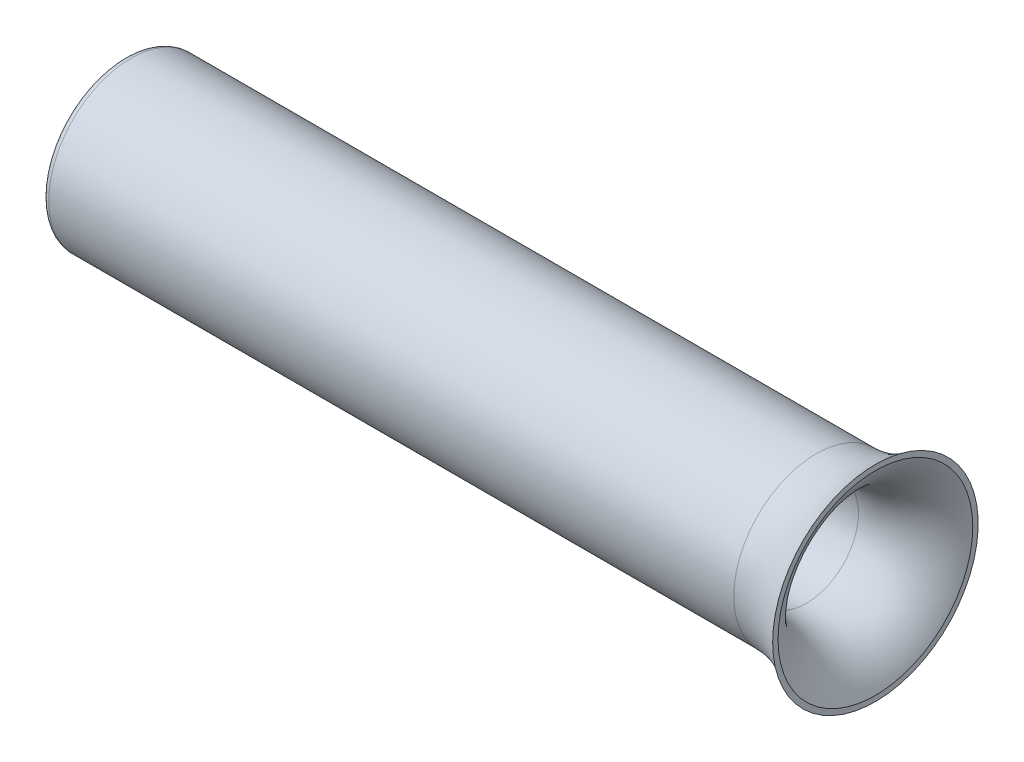
SolidWorks part; units mm, degrees
ref_plane "Front Plane" through (0, 0, 0) normal (0, 0, 1) x (1, 0, 0)
ref_plane "Top Plane" through (0, 0, 0) normal (0, 1, 0) x (1, 0, 0)
ref_plane "Right Plane" through (0, 0, 0) normal (1, 0, 0) x (0, 0, -1)
sketch "Sketch1" plane through (0, 0, 0) normal (0, 0, 1) x (1, 0, 0)
  line L0 (0, 3.95) -> (57, 3.95)
  line L1 (57, 3.95) -> (57, 7.8)
  line L2 (0, 3.95) -> (0, 6.25)
  line L3 (0, 6.25) -> (52.5, 6.25)
  line L6 (0, 0) -> (20.2034, 0) construction
  arc A0 (57, 7.8) -> (52.5, 6.25) centre (52.5, 13.5573) cw
  arc A1 (57, 7.3916) -> (51.7648, 3.95) centre (51.7648, 9.6526) cw
  dimension "D1" = 6.25
  dimension "D2" = 3.95
  dimension "D3" = 57
  dimension "D4" = 4.5
  dimension "D5" = 7.8
revolve "Revolve1" add sketch "Sketch1" angle 360 about L6
fillet "Fillet1" radius 0.5 2 edges at (0, 0, 6.25) (0, 0, 3.95)
